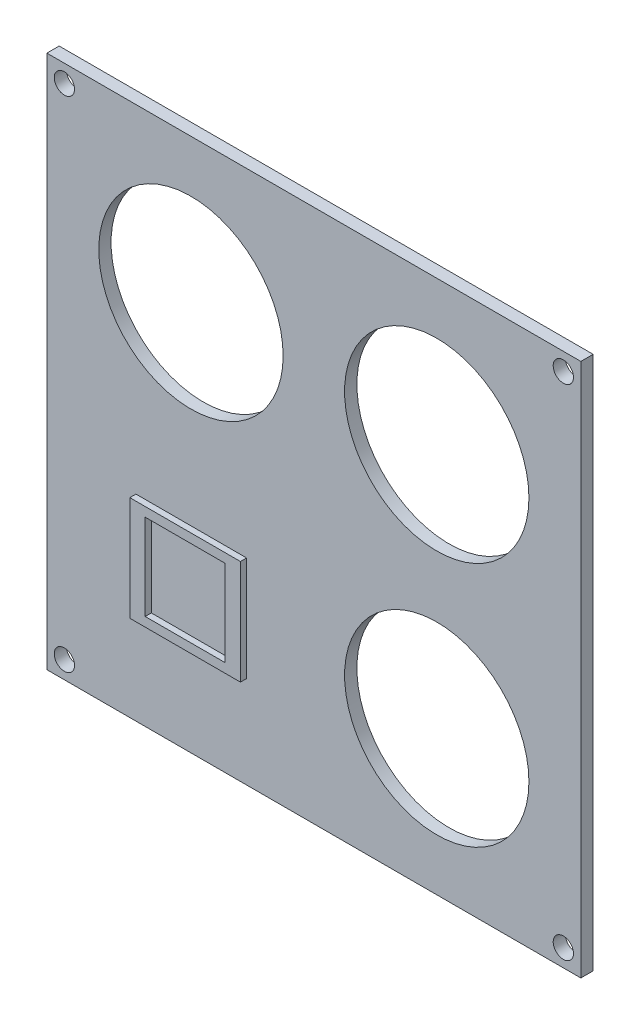
SolidWorks part; units mm, degrees
ref_plane "Front Plane" through (0, 0, 0) normal (1, 0, 0) x (0, 1, 0)
ref_plane "Top Plane" through (0, 0, 0) normal (0, 0, 1) x (0, 1, 0)
ref_plane "Right Plane" through (0, 0, 0) normal (0, 1, 0) x (-1, 0, 0)
sketch "Sketch1" plane through (0, 0, 0) normal (0, 0, 1) x (0, 1, 0)
  line L1 (0, 0) -> (86.9, 0)
  line L2 (0, 0) -> (0, 86.9)
  line L3 (0, 86.9) -> (86.9, 86.9)
  line L4 (86.9, 0) -> (86.9, 86.9)
  dimension "D1" = 86.9
  dimension "D2" = 86.9
extrude "Boss-Extrude1" add sketch "Sketch1" along normal blind 2 contours L3 L4 L1 L2
sketch "Sketch2" plane through (0, 0, 2) normal (0, 0, 1) x (1, 0, 0)
  line L0 (0, 0) -> (-86.9, 0) construction
  line L1 (-84.05, 84.05) -> (-2.85, 84.05) construction
  line L2 (-84.05, 84.05) -> (-84.05, 2.85) construction
  line L3 (-84.05, 2.85) -> (-2.85, 2.85) construction
  line L4 (-2.85, 84.05) -> (-2.85, 2.85) construction
  line L5 (0, 0) -> (0, 86.9) construction
  circle A0 centre (-84.05, 2.85) radius 1.65
  circle A1 centre (-2.85, 2.85) radius 1.65
  circle A2 centre (-2.85, 84.05) radius 1.65
  circle A3 centre (-84.05, 84.05) radius 1.65
  dimension "D3" = 3.3
  dimension "D1" = 81.2
  dimension "D2" = 81.2
  dimension "D4" = 2.85
  dimension "D5" = 2.85
extrude "Cut-Extrude3" cut sketch "Sketch2" against normal through all
sketch "Sketch3" plane through (0, 0, 2) normal (0, 0, 1) x (1, 0, 0)
  line L0 (0, 0) -> (-86.9, 0) construction
  line L1 (-72.4, 15) -> (-54.4, 15)
  line L2 (-72.4, 15) -> (-72.4, 32)
  line L3 (-72.4, 32) -> (-54.4, 32)
  line L4 (-54.4, 15) -> (-54.4, 32)
  line L6 (-72.4, 32) -> (-54.4, 15) construction
  line L7 (-86.9, 0) -> (-63.4, 23.5) construction
  dimension "D1" = 17
  dimension "D2" = 18
  dimension "D3" = 33.234
  dimension "D4" = 45
extrude "Boss-Extrude2" add sketch "Sketch3" along normal blind 1
sketch "Sketch4" plane through (0, 0, 3) normal (0, 0, 1) x (1, 0, 0)
  line L1 (-69.9, 30.5) -> (-56.9, 30.5)
  line L2 (-69.9, 30.5) -> (-69.9, 16.5)
  line L3 (-69.9, 16.5) -> (-56.9, 16.5)
  line L4 (-56.9, 30.5) -> (-56.9, 16.5)
  line L5 (-72.4, 32) -> (-54.4, 15) construction
  line L6 (-69.9, 16.5) -> (-56.9, 30.5) construction
  point P8 (-63.4, 23.5)
  point P9 (-63.4, 23.5)
  dimension "D1" = 13
  dimension "D2" = 14
extrude "Cut-Extrude4" cut sketch "Sketch4" against normal blind 1
sketch "Sketch5" plane through (0, 0, 2) normal (0, 0, 1) x (1, 0, 0)
  line L0 (-86.9, 86.9) -> (0, 0) construction
  line L1 (-86.9, 0) -> (0, 86.9) construction
  line L2 (-63.45, 63.45) -> (-23.45, 63.45) construction
  line L3 (-23.45, 63.45) -> (-23.45, 23.45) construction
  circle A0 centre (-63.45, 63.45) radius 15
  circle A1 centre (-23.45, 63.45) radius 15
  circle A2 centre (-23.45, 23.45) radius 15
  dimension "D1" = 30
  dimension "D2" = 40
extrude "Cut-Extrude5" cut sketch "Sketch5" against normal blind 2
